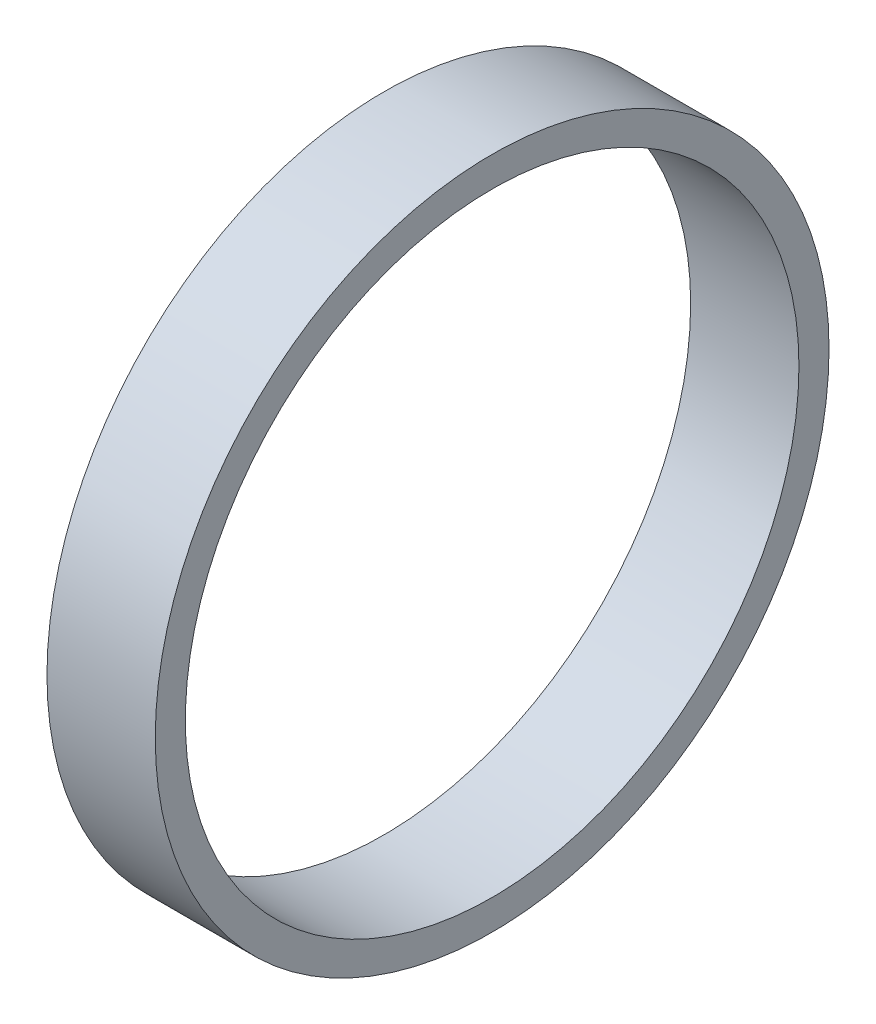
SolidWorks part; units mm, degrees
ref_plane "Vorne" through (0, 0, 0) normal (0, 0, 1) x (1, 0, 0)
ref_plane "Oben" through (0, 0, 0) normal (0, 1, 0) x (1, 0, 0)
ref_plane "Seite" through (0, 0, 0) normal (1, 0, 0) x (0, 0, -1)
sketch "Skizze1" plane through (0, 0, 0) normal (1, 0, 0) x (0, 0, -1)
  circle A0 centre (0, 0) radius 5.1
  circle A1 centre (0, 0) radius 5.6
  dimension "D1" = 10.2
  dimension "D2" = 11.2
extrude "Aufsatz-Linear austragen1" add sketch "Skizze1" along normal blind 1.8
